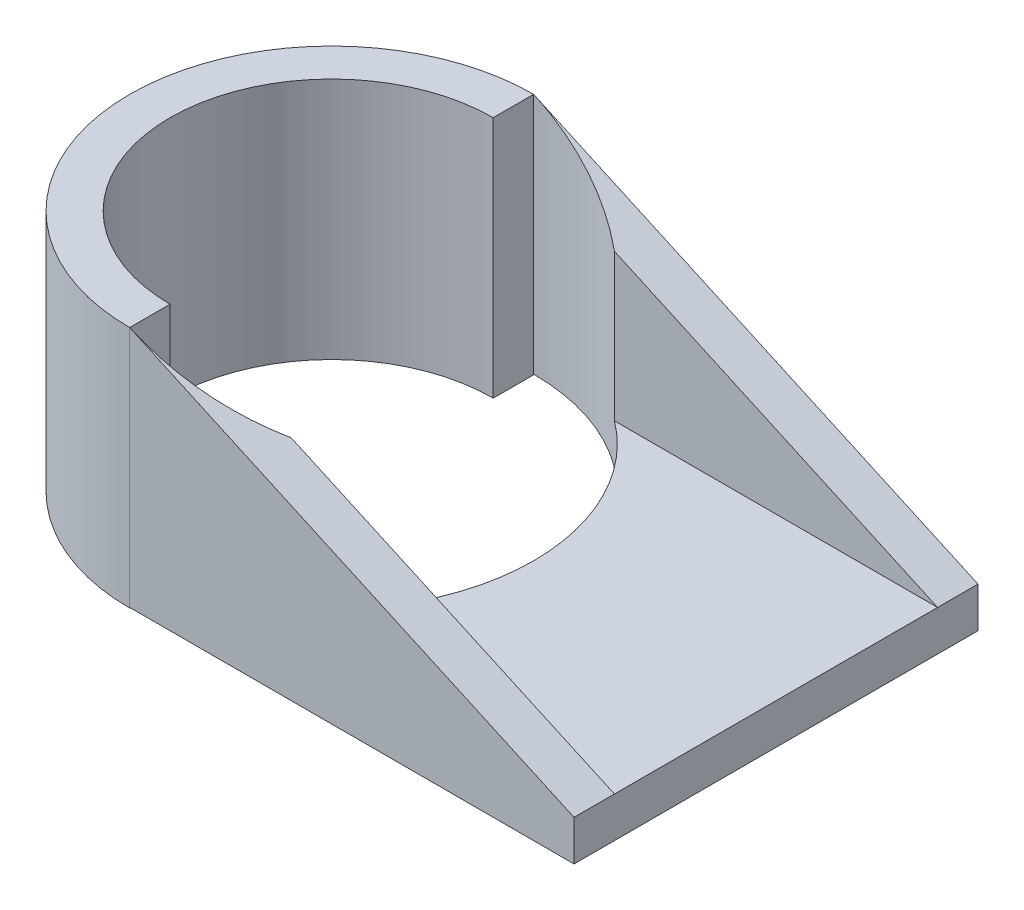
SolidWorks part; units mm, degrees
ref_plane "Front Plane" through (0, 0, 0) normal (0, 0, 1) x (1, 0, 0)
ref_plane "Top Plane" through (0, 0, 0) normal (0, 1, 0) x (1, 0, 0)
ref_plane "Right Plane" through (0, 0, 0) normal (1, 0, 0) x (0, 0, -1)
sketch "Sketch2" plane through (0, 0, 0) normal (0, 1, 0) x (1, 0, 0)
  line L1 (-55, 50) -> (55, 50)
  line L2 (-55, 50) -> (-55, -50)
  line L3 (-55, -50) -> (55, -50)
  line L4 (55, 50) -> (55, -50)
  line L5 (-55, 50) -> (55, -50) construction
  line L6 (-55, -50) -> (55, 50) construction
  point P0 (0, 0)
  dimension "D1" = 110
  dimension "D2" = 100
extrude "Boss-Extrude1" add sketch "Sketch2" along normal blind 10
sketch "Sketch3" plane through (0, 0, 50) normal (0, 0, 1) x (1, 0, 0)
  line L0 (-55, 10) -> (-55, 60)
  line L1 (-55, 60) -> (55, 10)
  line L2 (-55, 10) -> (55, 10)
  dimension "D1" = 50
extrude "Boss-Extrude2" add sketch "Sketch3" against normal blind 10
sketch "Sketch4" plane through (0, 0, -50) normal (0, 0, -1) x (-1, 0, 0)
  line L0 (55, 10) -> (55, 60)
  line L1 (55, 60) -> (-55, 10)
  line L2 (-55, 10) -> (55, 10)
extrude "Boss-Extrude3" add sketch "Sketch4" against normal blind 10
sketch "Sketch5" plane through (0, 10, 0) normal (0, 1, 0) x (1, 0, 0)
  line L3 (-55, 40) -> (-55, -40) construction
  circle A3 centre (-55, 0) radius 50
extrude "Boss-Extrude4" add sketch "Sketch5" along normal blind 50 and the other way blind 10.1365
sketch "Sketch6" plane through (0, 60, 0) normal (0, 1, 0) x (1, 0, 0)
  line L0 (-55, 50) -> (-55, -50)
  arc A0 (-55, -50) -> (-55, 50) centre (-55, 0) ccw
extrude "Cut-Extrude3" cut sketch "Sketch6" against normal blind 100
sketch "Sketch7" plane through (0, 60, 0) normal (0, 1, 0) x (1, 0, 0)
  line L0 (-55, 50) -> (-55, -50) construction
  line L1 (-55, 40) -> (-55, -40)
  arc A0 (-55, 40) -> (-55, -40) centre (-55, 0) ccw
  dimension "D1" = 80
extrude "Cut-Extrude4" cut sketch "Sketch7" against normal blind 100
sketch "Sketch8" plane through (0, 10, 0) normal (0, 1, 0) x (1, 0, 0)
  line L0 (-55, -40) -> (-25, -40)
  line L1 (-25, -40) -> (-25, -50)
  line L2 (55, -50) -> (-55, -50) construction
  line L3 (-25, -50) -> (-55, -50)
  line L4 (-55, 40) -> (-25, 40)
  line L5 (-25, 40) -> (-25, 50)
  line L6 (-55, 40) -> (-55, 50)
  line L7 (-55, -50) -> (-55, -40)
  line L10 (-55, 50) -> (55, 50) construction
  line L11 (-25, 50) -> (-55, 50)
  arc A2 (-55, 40) -> (-55, -40) centre (-55, 0) ccw
  arc A3 (-55, 50) -> (-55, -50) centre (-55, 0) ccw
  arc A4 (-55, 40) -> (-55, -40) centre (-55, 0) ccw
  arc A5 (-55, 50) -> (-55, -50) centre (-55, 0) ccw
  dimension "D1" = 0
